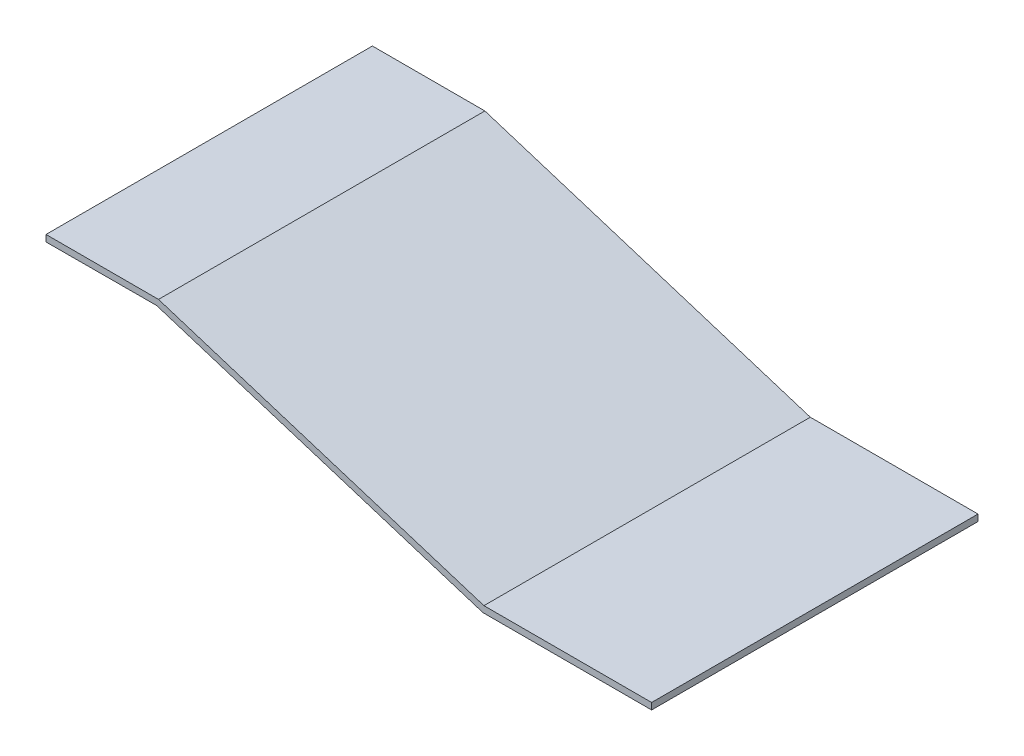
SolidWorks part; units mm, degrees
ref_plane "Front Plane" through (0, 0, 0) normal (0, 0, 1) x (1, 0, 0)
ref_plane "Top Plane" through (0, 0, 0) normal (0, 1, 0) x (1, 0, 0)
ref_plane "Right Plane" through (0, 0, 0) normal (1, 0, 0) x (0, 0, -1)
sketch "Sketch1" plane through (0, 0, 0) normal (0, 0, 1) x (1, 0, 0)
  line L0 (0, 56.6611) -> (0, 76.6611)
  line L1 (0, 76.6611) -> (344.7284, 76.6611)
  line L2 (344.7284, 76.6611) -> (1405.287, -257.4149)
  line L3 (1405.287, -257.4149) -> (1338.7195, -257.4149)
  line L4 (1338.7195, -257.4149) -> (338.7195, 57.5851)
  line L5 (338.7195, 57.5851) -> (0, 56.6611)
  line L6 (1338.7195, -257.4149) -> (1338.7195, -237.4149)
  line L7 (1338.7195, -237.4149) -> (1855.5883, -237.4149)
  line L8 (1855.5883, -237.4149) -> (1855.5883, -257.4149)
  line L9 (1855.5883, -257.4149) -> (1338.7195, -257.4149)
  point P9 (1855.5883, -257.4149)
  dimension "D1" = 20
  dimension "D2" = 20
  dimension "D4" = 315
  dimension "D5" = 20
  dimension "D6" = 1000
extrude "Boss-Extrude1" add sketch "Sketch1" along normal blind 1000 contours L6 L7 L8 L9 | L4 L5 L0 L1 L2 L3
